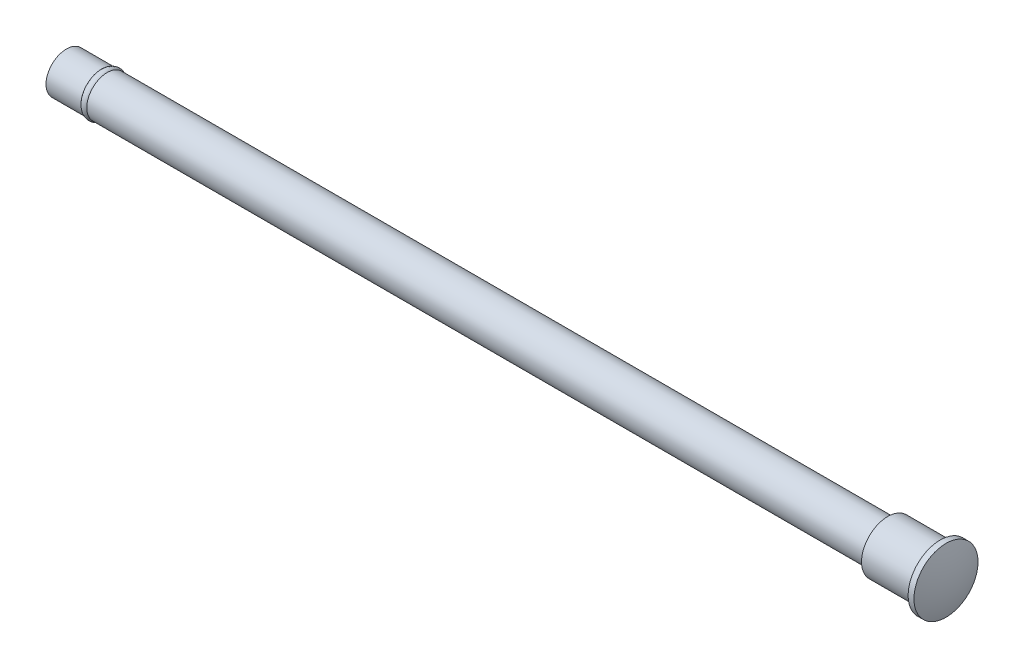
SolidWorks part; units mm, degrees
ref_plane "Front Plane" through (0, 0, 0) normal (0, 0, 1) x (1, 0, 0)
ref_plane "Top Plane" through (0, 0, 0) normal (0, 1, 0) x (1, 0, 0)
ref_plane "Right Plane" through (0, 0, 0) normal (1, 0, 0) x (0, 0, -1)
sketch "Sketch1" plane through (0, 0, 0) normal (0, 0, 1) x (1, 0, 0)
  line L0 (0, 0) -> (152, 0)
  line L1 (0, 0) -> (0, 3.5)
  line L2 (0, 3.5) -> (141, 3.5)
  line L3 (141, 3.5) -> (141, 4.5)
  line L4 (141, 4.5) -> (150, 4.5)
  line L5 (150, 4.5) -> (150, 5.5)
  line L6 (150, 5.5) -> (151, 5.5)
  line L7 (152, 0) -> (152, 36.8383) construction
  arc A0 (151, 5.5) -> (152, 0) centre (136.375, 0) cw
  dimension "D1" = 152
  dimension "D2" = 3.5
  dimension "D3" = 1
  dimension "D4" = 1
  dimension "D5" = 9
  dimension "D6" = 1
  dimension "D7" = 1
revolve "Revolve1" add sketch "Sketch1" angle 360 about L0
sketch "Sketch2" plane through (0, 0, 0) normal (0, 0, 1) x (1, 0, 0)
  line L0 (5.2921, 3.7) -> (8.6418, 3.7) construction
  line L1 (6, 0) -> (7, 0)
  line L2 (7, 0) -> (7, 3.5)
  line L3 (141, 3.5) -> (0, 3.5) construction
  line L4 (6, 0) -> (6, 3.5)
  arc A0 (6, 3.5) -> (7, 3.5) centre (6.5, 2.975) cw
  dimension "D1" = 6
  dimension "D2" = 1
  dimension "D3" = 0.2
revolve "Revolve2" add sketch "Sketch2" angle 360 about L1
sketch "Sketch3" plane through (0, 0, 0) normal (-1, 0, 0) x (0, 0, 1)
  circle A2 centre (0, 0) radius 2.2
  circle A3 centre (0, 0) radius 2.2
  dimension "D1" = 1.3
extrude "Cut-Extrude1" cut sketch "Sketch3" against normal up to surface (150 mm away) up to face at (150, 0, 4.5)
